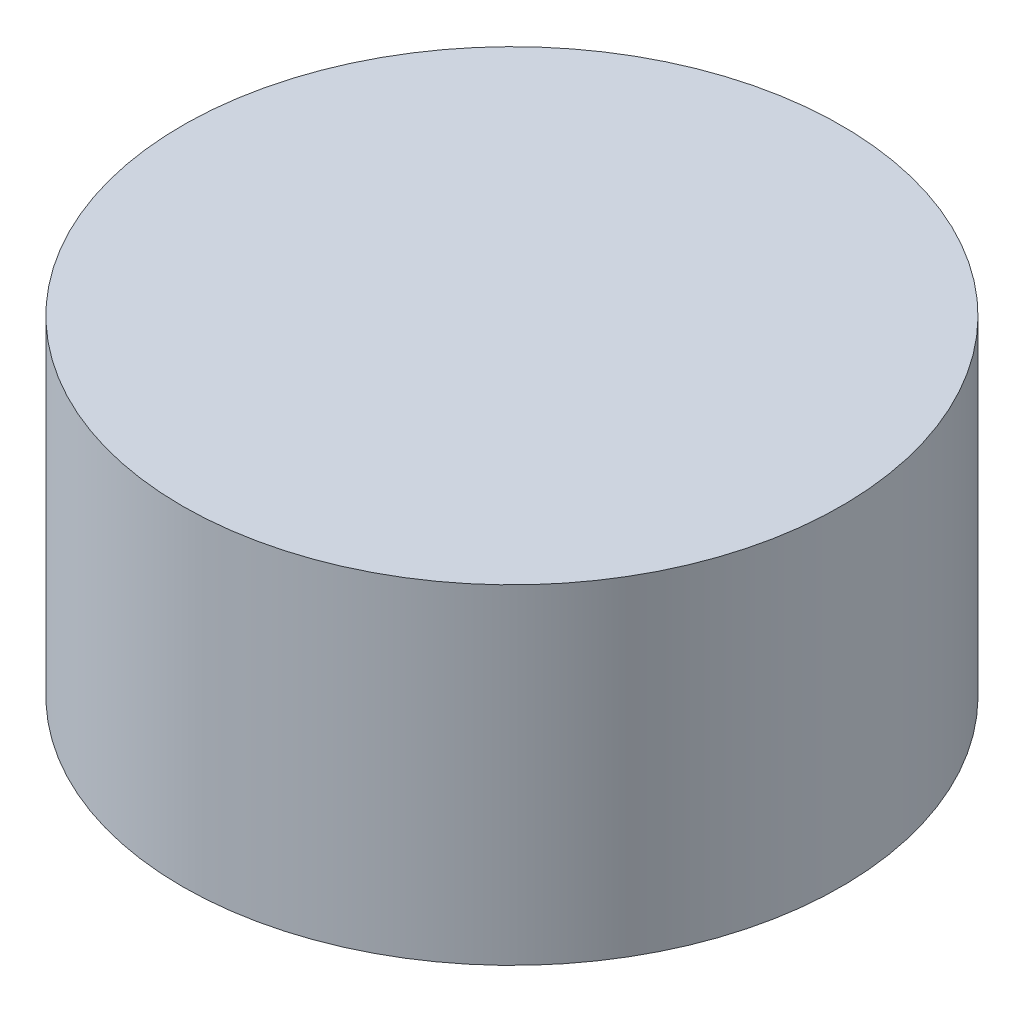
SolidWorks part; units mm, degrees
ref_plane "Front Plane" through (0, 0, 0) normal (0, 0, 1) x (1, 0, 0)
ref_plane "Top Plane" through (0, 0, 0) normal (0, 1, 0) x (1, 0, 0)
ref_plane "Right Plane" through (0, 0, 0) normal (1, 0, 0) x (0, 0, -1)
sketch "Sketch1" plane through (0, 0, 0) normal (0, 1, 0) x (1, 0, 0)
  circle A0 centre (0, 0) radius 3
  dimension "D1" = 6
extrude "Boss-Extrude1" add sketch "Sketch1" along normal blind 3
equation "\"Diameter\" = 6"
equation "\"D1@Sketch1\"=\"Diameter\""
equation "\"Depth\" = 3"
equation "\"D1@Boss-Extrude1\"=\"Depth\""
